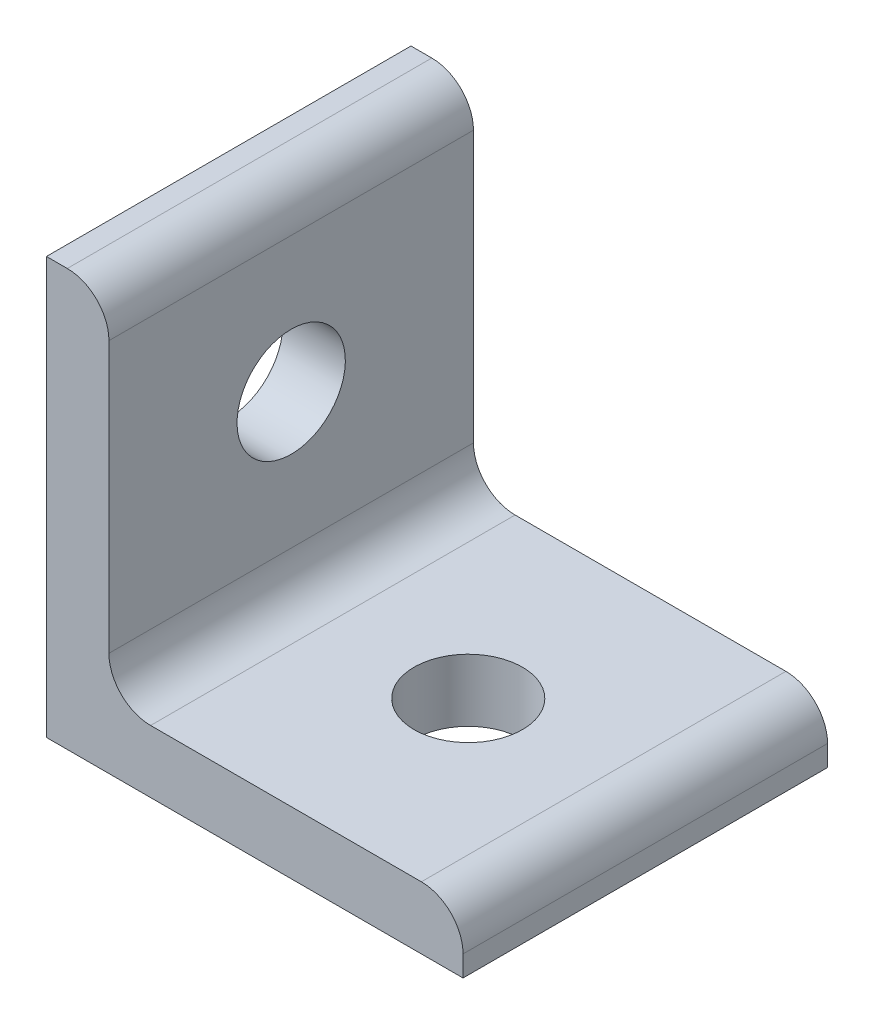
SolidWorks part; units mm, degrees
ref_plane "Front Plane" through (0, 0, 0) normal (0, 0, 1) x (1, 0, 0)
ref_plane "Top Plane" through (0, 0, 0) normal (0, 1, 0) x (1, 0, 0)
ref_plane "Right Plane" through (0, 0, 0) normal (1, 0, 0) x (0, 0, -1)
sketch "Sketch1" plane through (0, 0, 0) normal (0, 0, 1) x (1, 0, 0)
  line L0 (0, 21.59) -> (0, 0)
  line L1 (0, 0) -> (21.59, 0)
  line L2 (21.59, 0) -> (21.59, -3.81)
  line L3 (21.59, -3.81) -> (-3.81, -3.81)
  line L4 (-3.81, -3.81) -> (-3.81, 21.59)
  line L5 (-3.81, 21.59) -> (0, 21.59)
  dimension "D1" = 25.4
  dimension "D2" = 25.4
  dimension "D3" = 3.81
extrude "Boss-Extrude1" add sketch "Sketch1" along normal blind 22.225
sketch "Sketch2" plane through (0, 0, 0) normal (0, 1, 0) x (1, 0, 0)
  line L0 (21.59, 0) -> (0, 0) construction
  line L1 (21.59, -22.225) -> (21.59, 0) construction
  circle A0 centre (10.795, -11.1125) radius 3.302
  point P2 (10.795, 0)
  point P3 (21.59, -11.1125)
  point P6 (0, 0)
  point P9 (0, 0)
  point P10 (0, 0)
  dimension "D1" = 6.604
extrude "Cut-Extrude1" cut sketch "Sketch2" against normal through all
sketch "Sketch3" plane through (0, 0, 0) normal (1, 0, 0) x (0, 0, -1)
  line L1 (0, 0) -> (0, 21.59) construction
  line L2 (-22.225, 21.59) -> (0, 21.59) construction
  circle A0 centre (-11.1125, 10.795) radius 3.302
  point P2 (-11.1125, 21.59)
  point P3 (0, 10.795)
  point P4 (0, 0)
  dimension "D1" = 6.604
extrude "Cut-Extrude2" cut sketch "Sketch3" against normal through all
fillet "Fillet1" radius 2.54 3 edges at (21.59, 0, 11.1125) (0, 21.59, 11.1125) (0, 0, 11.1125)
